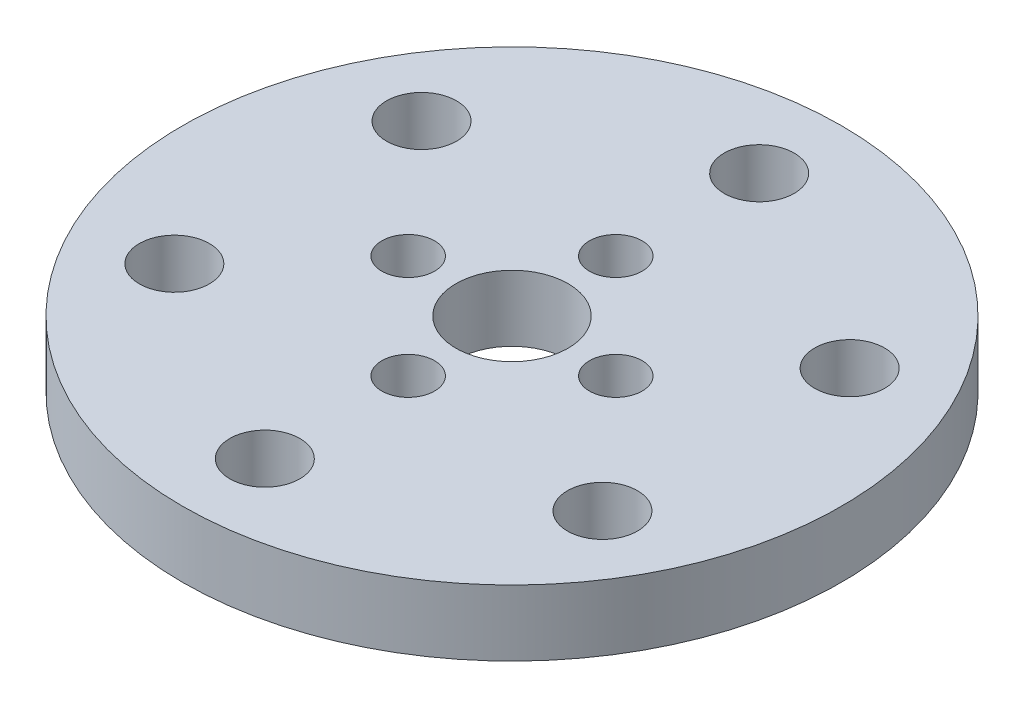
SolidWorks part; units mm, degrees
ref_plane "Front Plane" through (0, 0, 0) normal (0, 0, 1) x (1, 0, 0)
ref_plane "Top Plane" through (0, 0, 0) normal (0, 1, 0) x (1, 0, 0)
ref_plane "Right Plane" through (0, 0, 0) normal (1, 0, 0) x (0, 0, -1)
sketch "Sketch1" plane through (0, 0, 0) normal (0, 1, 0) x (1, 0, 0)
  circle A0 centre (0, 0) radius 25.4
  dimension "D1" = 50.8
extrude "Boss-Extrude1" add sketch "Sketch1" along normal blind 5.08
sketch "Sketch2" plane through (0, 5.08, 0) normal (0, 1, 0) x (1, 0, 0)
  circle A0 centre (0, -19.05) radius 2.6987
  circle A1 centre (-16.4978, -9.525) radius 2.6987
  circle A2 centre (-16.4978, 9.525) radius 2.6987
  circle A3 centre (0, 19.05) radius 2.6987
  circle A4 centre (16.4978, 9.525) radius 2.6987
  circle A5 centre (16.4978, -9.525) radius 2.6987
  point P15 (0, 0)
  dimension "D1" = 5.3975
  dimension "D2" = 19.05
  dimension "D3" = 6
extrude "Cut-Extrude1" cut sketch "Sketch2" against normal blind 5.08
sketch "Sketch3" plane through (0, 0, 0) normal (0, -1, 0) x (1, 0, 0)
  circle A0 centre (0, 0) radius 4.318
  circle A1 centre (0, -8.001) radius 2.032
  circle A2 centre (-8.001, 0) radius 2.032
  circle A3 centre (0, 8.001) radius 2.032
  circle A4 centre (8.001, 0) radius 2.032
  point P14 (0, 0)
  dimension "D1" = 8.001
  dimension "D2" = 4
extrude "Cut-Extrude2" cut sketch "Sketch3" against normal blind 5.08
